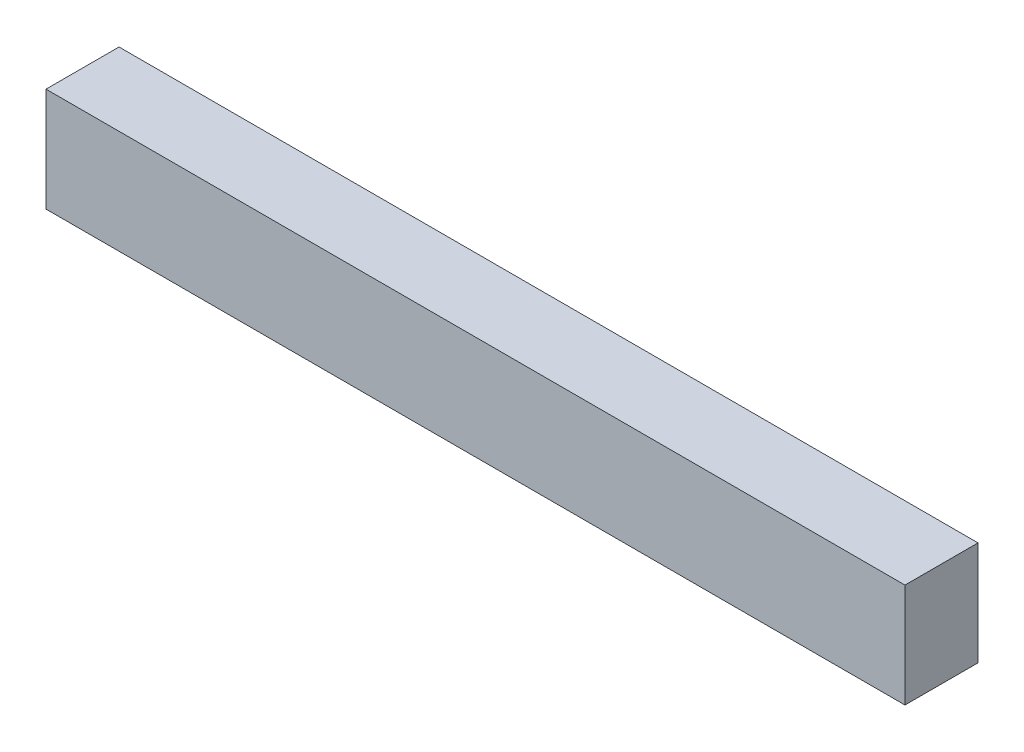
SolidWorks part; units mm, degrees
ref_plane "Front Plane" through (0, 0, 0) normal (0, 0, 1) x (1, 0, 0)
ref_plane "Top Plane" through (0, 0, 0) normal (0, 1, 0) x (1, 0, 0)
ref_plane "Right Plane" through (0, 0, 0) normal (1, 0, 0) x (0, 0, -1)
sketch "Sketch1" plane through (0, 0, 0) normal (0, 0, 1) x (1, 0, 0)
  line L0 (-6.4262, 0.7112) -> (5.334, 0.7112)
  line L1 (5.334, 0.7112) -> (5.334, -0.7112)
  line L2 (5.334, -0.7112) -> (-6.4262, -0.7112)
  line L3 (-6.4262, -0.7112) -> (-6.4262, 0.7112)
extrude "Component_Outline" add sketch "Sketch1" along normal blind 1 separate body
sketch3d "3DSketch1"
  line L0 (0, 0, 0) -> (1, 0, 0)
  line L1 (0, 0, 0) -> (0, 1, 0)
  line L2 (0, 0, 0) -> (0, 0, 1)
  point P0 (0, 0, 0)
